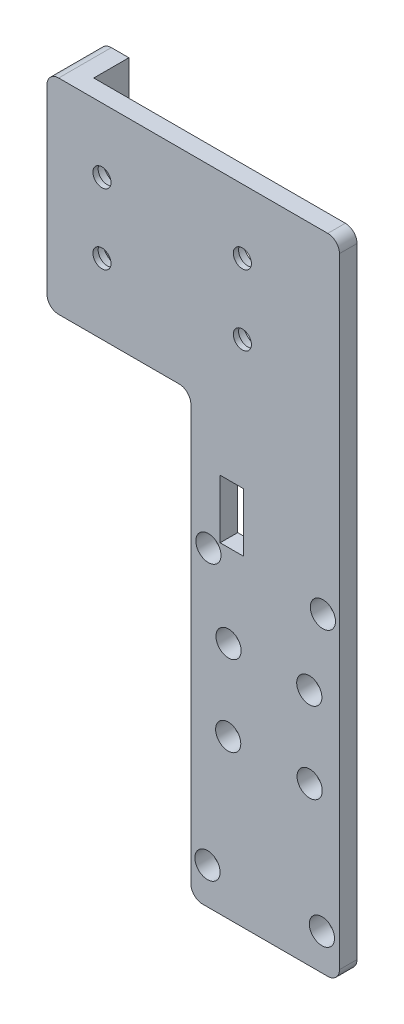
SolidWorks part; units mm, degrees
material "ABS"
ref_plane "Plan de face" through (0, 0, 0) normal (0, 0, 1) x (1, 0, 0)
ref_plane "Plan de dessus" through (0, 0, 0) normal (0, 1, 0) x (1, 0, 0)
ref_plane "Plan de droite" through (0, 0, 0) normal (1, 0, 0) x (0, 0, -1)
sketch "Esquisse1" plane through (0, 0, 0) normal (0, 0, 1) x (1, 0, 0)
  line L1 (0, 0) -> (26.7508, 0)
  line L2 (1.3508, -35) -> (1.3508, -109.9917)
  line L3 (1.3508, -109.9917) -> (26.7508, -109.9917)
  line L4 (26.7508, 0) -> (26.7508, -109.9917)
  line L9 (1.3508, -35) -> (-23.2492, -35)
  line L11 (0, 0) -> (-23.2492, 0)
  line L12 (-23.2492, -35) -> (-23.2492, 0)
  point P4 (-23.2492, -17.5)
  dimension "D1" = 110
  dimension "D2" = 25.4
  dimension "D3" = 50
  dimension "D4" = 35
extrude "Boss.-Extru.1" add sketch "Esquisse1" along normal blind 3
hole_wizard "Dégagement #61" positions "Esquisse3" profile "Esquisse4" hole size "#6" standard "Ansi Inch" end condition up to next
sketch "Esquisse3" plane through (0, 0, 3) normal (0, 0, 1) x (1, 0, 0)
  line L0 (26.7508, -109.9917) -> (26.7508, 0) construction
  line L1 (1.3508, -109.9917) -> (26.7508, -109.9917) construction
  point P0 (21.5889, -69.1917)
  point P2 (7.7889, -69.1917)
  point P4 (7.7297, -82.9917)
  point P6 (21.6508, -82.9917)
  dimension "D1" = 19.558
  dimension "D2" = 19.56
  dimension "D3" = 13.8
  dimension "D4" = 13.8
  dimension "D5" = 13.8
  dimension "D6" = 27
  dimension "D7" = 5.1
  dimension "D8" = 27
sketch "Esquisse4" plane through (21.5889, -69.1917, 3) normal (1, 0, 0) x (0, -1, 0)
  line L0 (0, 0) -> (0, 3)
  line L1 (0, 3) -> (2.1526, 3)
  line L2 (2.1526, 3) -> (2.1526, 0)
  line L5 (2.1526, 0) -> (0, 0)
  line L11 (0, -6.35) -> (0, 107.95) construction
  dimension "Diamètre du perçage jusqu'au prochain" = 4.3053
  dimension "Profondeur du perçage jusqu'au prochain" = 3
hole_wizard "Chambrage pour vis à tête ronde bombée M2.51" positions "Esquisse5" profile "Esquisse6" counterbore size "M2.5" standard "Ansi Metric" end condition up to next
sketch "Esquisse5" plane through (0, 0, 0) normal (0, 0, -1) x (-1, 0, 0)
  line L0 (-26.7508, 0) -> (23.2492, 0) construction
  line L1 (23.2492, 0) -> (23.2492, -35) construction
  point P0 (13.8492, -23)
  point P2 (13.8492, -11)
  point P4 (-10.1508, -11)
  point P6 (-10.1508, -23)
  dimension "D1" = 11
  dimension "D2" = 9.4
  dimension "D3" = 12
  dimension "D4" = 24
  dimension "D5" = 12
  dimension "D6" = 24
  dimension "D7" = 11
  dimension "D8" = 9.4
sketch "Esquisse6" plane through (-13.8492, -23, 0) normal (1, 0, 0) x (0, 1, 0)
  line L0 (0, 0) -> (0, 3)
  line L1 (0, 3) -> (1.55, 3)
  line L3 (1.55, 3) -> (1.55, 2.1)
  line L4 (1.55, 2.1) -> (3, 2.1)
  line L5 (3, 2.1) -> (3, 0)
  line L7 (3, 0) -> (0, 0)
  line L11 (0, -6.35) -> (0, 107.95) construction
  dimension "Diamètre du perçage jusqu'au prochain" = 3.1
  dimension "Profondeur du perçage jusqu'au prochain" = 3
  dimension "Diamètre du chambrage" = 6
  dimension "Profondeur du chambrage" = 2.1
sketch "Esquisse7" plane through (0, 0, 0) normal (0, 0, -1) x (-1, 0, 0)
  line L0 (-11.7508, -65) -> (-11.7508, -35)
  line L2 (-16.7508, -30) -> (-16.7508, -65)
  line L3 (-16.7508, -65) -> (-11.7508, -65)
  line L9 (-11.7508, -35) -> (23.2492, -35)
  line L11 (-16.7508, -30) -> (18.2492, -30)
  line L14 (23.2492, -35) -> (23.2492, 0)
  line L15 (23.2492, 0) -> (18.2492, 0)
  line L16 (18.2492, -30) -> (18.2492, 0)
  line L21 (-16.7508, -89.9917) -> (-11.7508, -89.9917)
  line L22 (-16.7508, -89.9917) -> (-16.7508, -109.9917)
  line L23 (-16.7508, -109.9917) -> (-11.7508, -109.9917)
  line L24 (-11.7508, -89.9917) -> (-11.7508, -109.9917)
  line L29 (-26.7508, -109.9917) -> (-26.7508, 0) construction
  line L30 (-1.3508, -109.9917) -> (-26.7508, -109.9917) construction
  dimension "D1" = 5
  dimension "D2" = 5
  dimension "D3" = 5
  dimension "D4" = 10
  dimension "D5" = 5
  dimension "D6" = 35
  dimension "D7" = 20
  dimension "D8" = 10
  dimension "D9" = 0
extrude "Boss.-Extru.2" add sketch "Esquisse7" along normal blind 6
sketch "Esquisse8" plane through (11.7508, 0, 0) normal (-1, 0, 0) x (0, 0, 1)
  line L0 (-6, -65) -> (-6, -35) construction
  line L1 (-4, -48) -> (-2, -48)
  line L2 (-4, -48) -> (-4, -54)
  line L3 (-4, -54) -> (-2, -54)
  line L4 (-2, -48) -> (-2, -54)
  line L5 (-6, -65) -> (0, -65) construction
  dimension "D1" = 6
  dimension "D2" = 2
  dimension "D3" = 2
  dimension "D4" = 11
extrude "Enlèv. mat.-Extru.1" cut sketch "Esquisse8" against normal up to next
sketch "Esquisse9" plane through (0, -35, 0) normal (0, -1, 0) x (1, 0, 0)
  line L0 (11.7508, -6) -> (-23.2492, -6) construction
  line L1 (-0.2492, -4) -> (-6.2492, -4)
  line L2 (-0.2492, -4) -> (-0.2492, -2)
  line L3 (-0.2492, -2) -> (-6.2492, -2)
  line L4 (-6.2492, -4) -> (-6.2492, -2)
  line L5 (11.7508, -6) -> (11.7508, 0) construction
  dimension "D1" = 6
  dimension "D2" = 2
  dimension "D3" = 2
  dimension "D4" = 12
extrude "Enlèv. mat.-Extru.2" cut sketch "Esquisse9" against normal up to next
sketch "Esquisse10" plane through (-23.2492, 0, 0) normal (-1, 0, 0) x (0, 0, 1)
  line L0 (-6, -35) -> (-6, 0) construction
  line L1 (-4, -14) -> (-2, -14)
  line L2 (-4, -14) -> (-4, -20)
  line L3 (-4, -20) -> (-2, -20)
  line L4 (-2, -14) -> (-2, -20)
  line L5 (3, -35) -> (-6, -35) construction
  dimension "D1" = 6
  dimension "D2" = 2
  dimension "D3" = 2
  dimension "D4" = 15
extrude "Enlèv. mat.-Extru.3" cut sketch "Esquisse10" against normal up to next
fillet "Congé1" radius 2 9 edges at (-18.2492, -30, -3) (16.7508, -30, -3) (11.7508, -35, -3) (1.3508, -35, 1.5) (26.7508, -109.9917, 1.5) (1.3508, -109.9917, 1.5) (-23.2492, 0, -1.5) (26.7508, 0, 1.5) (-23.2492, -35, -1.5)
hole_wizard "Dégagement #65" positions "Esquisse11" profile "Esquisse12" hole size "#6" standard "Ansi Inch" end condition through all
sketch "Esquisse11" plane through (0, 0, 0) normal (0, 0, -1) x (-1, 0, 0)
  line L0 (-26.7508, -107.9917) -> (-26.7508, -2) construction
  line L1 (-16.7508, -109.9917) -> (-24.7508, -109.9917) construction
  line L2 (-3.3508, -109.9917) -> (-11.7508, -109.9917) construction
  point P0 (-23.7508, -103.7917)
  point P2 (-4.1908, -103.7917)
  dimension "D1" = 3
  dimension "D2" = 6.2
  dimension "D3" = 19.56
  dimension "D4" = 6.2
sketch "Esquisse12" plane through (23.7508, -103.7917, 0) normal (1, 0, 0) x (0, 1, 0)
  line L0 (0, 0) -> (0, 3)
  line L1 (0, 3) -> (2.1526, 3)
  line L2 (2.1526, 3) -> (2.1526, 0)
  line L5 (2.1526, 0) -> (0, 0)
  line L11 (0, -6.35) -> (0, 107.95) construction
  dimension "Diamètre du perçage jusqu'au prochain" = 4.3053
  dimension "Profondeur du perçage jusqu'au prochain" = 3
hole_wizard "Dégagement #64" positions "Esquisse13" profile "Esquisse14" hole size "#6" standard "Ansi Inch" end condition up to next
sketch "Esquisse13" plane through (0, 0, 0) normal (0, 0, -1) x (-1, 0, 0)
  line L0 (-1.3508, -37) -> (-1.3508, -107.9917) construction
  line L1 (-16.7508, -109.9917) -> (-24.7508, -109.9917) construction
  line L2 (-3.3508, -109.9917) -> (-11.7508, -109.9917) construction
  point P0 (-23.9108, -56.7917)
  point P2 (-4.3508, -56.7917)
  dimension "D1" = 3
  dimension "D2" = 19.56
  dimension "D3" = 53.2
  dimension "D4" = 53.2
sketch "Esquisse14" plane through (23.9108, -56.7917, 0) normal (1, 0, 0) x (0, 1, 0)
  line L0 (0, 0) -> (0, 3)
  line L1 (0, 3) -> (2.1526, 3)
  line L2 (2.1526, 3) -> (2.1526, 0)
  line L5 (2.1526, 0) -> (0, 0)
  line L11 (0, -6.35) -> (0, 107.95) construction
  dimension "Diamètre du perçage jusqu'au prochain" = 4.3053
  dimension "Profondeur du perçage jusqu'au prochain" = 3
sketch "Esquisse15" plane through (0, 0, 3) normal (0, 0, 1) x (1, 0, 0)
  line L0 (1.3508, -37) -> (1.3508, -107.9917) construction
  line L1 (10.3508, -55) -> (6.3508, -55)
  line L2 (10.3508, -55) -> (10.3508, -45)
  line L3 (10.3508, -45) -> (6.3508, -45)
  line L4 (6.3508, -55) -> (6.3508, -45)
  line L5 (10.3508, -55) -> (6.3508, -45) construction
  line L6 (10.3508, -45) -> (6.3508, -55) construction
  line L7 (-21.2492, -35) -> (-0.6492, -35) construction
  point P0 (8.3508, -50)
  dimension "D1" = 4
  dimension "D2" = 10
  dimension "D3" = 7
  dimension "D4" = 15
extrude "Enlèv. mat.-Extru.4" cut sketch "Esquisse15" against normal blind 10
